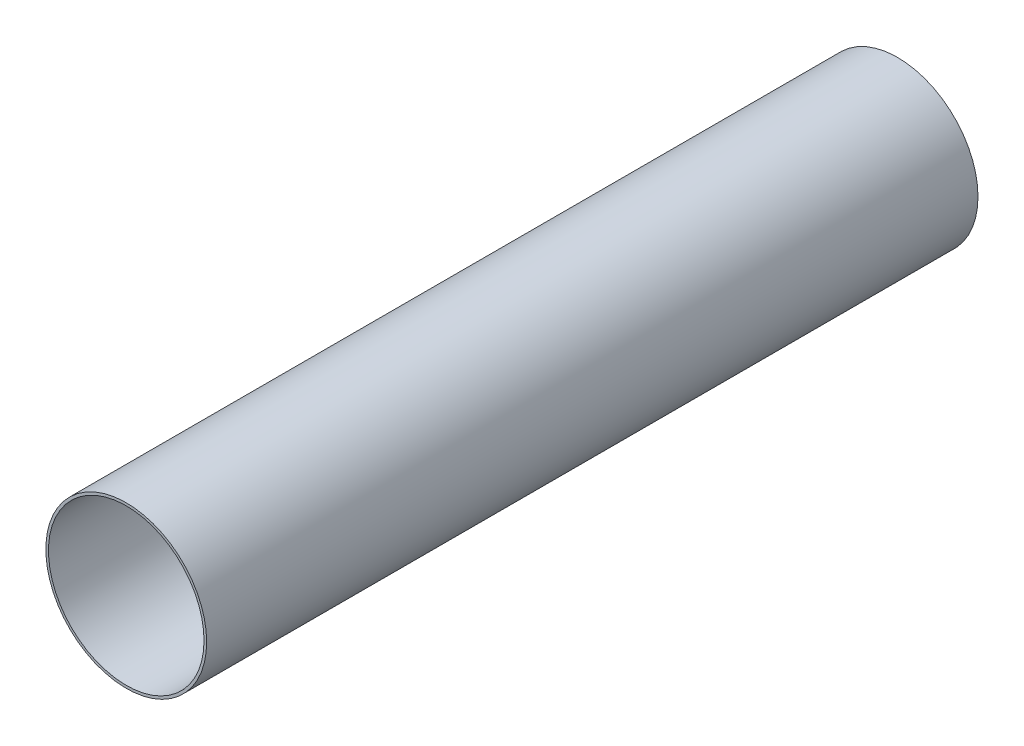
SolidWorks part; units mm, degrees
ref_plane "Front Plane" through (0, 0, 0) normal (0, 0, 1) x (1, 0, 0)
ref_plane "Top Plane" through (0, 0, 0) normal (0, 1, 0) x (1, 0, 0)
ref_plane "Right Plane" through (0, 0, 0) normal (1, 0, 0) x (0, 0, -1)
sketch "Sketch1" plane through (0, 0, 0) normal (0, 0, 1) x (1, 0, 0)
  circle A0 centre (0, 0) radius 61.5
  circle A1 centre (0, 0) radius 59.5
  dimension "D1" = 123
  dimension "D2" = 2
extrude "Boss-Extrude1" add sketch "Sketch1" along normal mid plane 590
